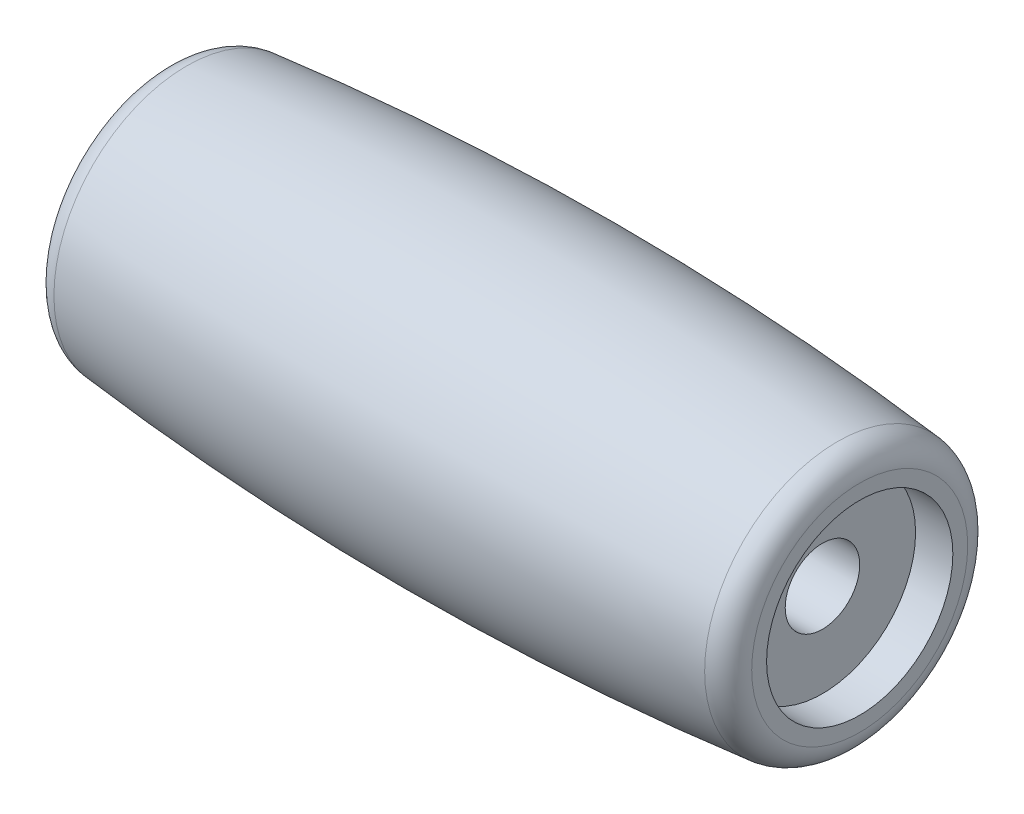
SolidWorks part; units mm, degrees
ref_plane "Plan de face" through (0, 0, 0) normal (0, 0, 1) x (1, 0, 0)
ref_plane "Plan de dessus" through (0, 0, 0) normal (0, 1, 0) x (1, 0, 0)
ref_plane "Plan de droite" through (0, 0, 0) normal (1, 0, 0) x (0, 0, -1)
sketch "Esquisse1" plane through (0, 0, 0) normal (0, 0, 1) x (1, 0, 0)
  line L0 (0, 6) -> (0, 0) construction
  line L1 (0, 0) -> (14.6958, 0) construction
  line L2 (-12.5, 1.5) -> (12.5, 1.5)
  line L3 (12.5, 1.5) -> (12.5, 3.75)
  line L4 (12.5, 3.75) -> (14, 3.75)
  line L5 (14, 3.75) -> (14, 4.3486)
  line L6 (-14, 3.75) -> (-14, 4.3486)
  line L7 (-12.5, 3.75) -> (-14, 3.75)
  line L8 (-12.5, 1.5) -> (-12.5, 3.75)
  arc A0 (-13.1, 5.3436) -> (13.1, 5.3436) centre (0, -125.0417) cw
  arc A1 (-14, 4.3486) -> (-13.1, 5.3436) centre (-13, 4.3486) cw
  arc A2 (14, 4.3486) -> (13.1, 5.3436) centre (13, 4.3486) ccw
  point P10 (0, 1.5)
  point P16 (-14, 5.25)
  point P19 (14, 5.25)
  dimension "D7" = 1
  dimension "D8" = 1
  dimension "D1" = 1.5
  dimension "D2" = 2.25
  dimension "D3" = 1.5
  dimension "D4" = 14
  dimension "D5" = 6
  dimension "D6" = 3
revolve "Révolution1" add sketch "Esquisse1" angle 360 about L1
